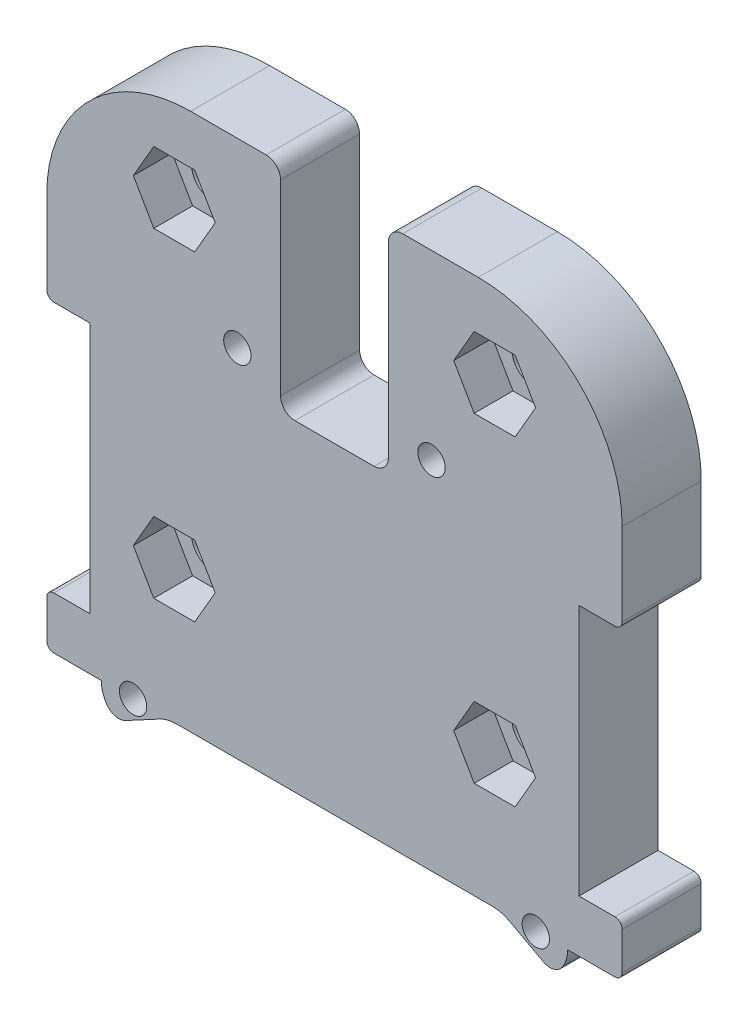
SolidWorks part; units mm, degrees
ref_plane "前视基准面" through (0, 0, 0) normal (0, 0, 1) x (1, 0, 0)
ref_plane "上视基准面" through (0, 0, 0) normal (0, 1, 0) x (1, 0, 0)
ref_plane "右视基准面" through (0, 0, 0) normal (1, 0, 0) x (0, 0, -1)
sketch "草图1" plane through (0, 0, 0) normal (0, 0, 1) x (1, 0, 0)
  line L0 (0, 0) -> (0, 36.8895) construction
  line L2 (-40, 50) -> (40, 50)
  line L3 (-40, 50) -> (-40, -50)
  line L4 (-40, -50) -> (40, -50)
  line L5 (40, 50) -> (40, -50)
  dimension "D1" = 80
  dimension "D2" = 100
  dimension "D3" = 40
  dimension "D4" = 50
extrude "凸台-拉伸1" add sketch "草图1" along normal blind 11 contours L2 L5 L4 L3
sketch "草图7" plane through (0, 0, 11) normal (0, 0, 1) x (1, 0, 0)
  line L0 (0, 0) -> (0, 50) construction
  line L1 (-40, 50) -> (40, 50) construction
  line L3 (-7.5, 50) -> (7.5, 50)
  line L4 (-7.5, 50) -> (-7.5, 20)
  line L5 (-7.5, 20) -> (7.5, 20)
  line L6 (7.5, 50) -> (7.5, 20)
  dimension "D1" = 30
  dimension "D2" = 15
  dimension "D3" = 7.5
extrude "切除-拉伸1" cut sketch "草图7" against normal blind 16
sketch "草图2" plane through (0, 0, 11) normal (0, 0, 1) x (1, 0, 0)
  line L0 (0, 0) -> (0, -50) construction
  line L1 (-40, -50) -> (40, -50) construction
  line L2 (-23.6474, -14.5) -> (32.5152, -14.5) construction
  line L3 (-25.0117, -34.5) -> (44.0357, -34.5) construction
  line L4 (-19.0329, -14.5) -> (-17.8955, -14.5)
  line L5 (17.8955, -14.5) -> (19.0329, -14.5)
  line L6 (17.8955, -34.5) -> (19.0329, -34.5)
  line L7 (-19.0329, -34.5) -> (-17.8955, -34.5)
  arc A0 (-17.8955, -14.5) -> (-17.8955, -34.5) centre (0, -24.5) ccw
  arc A1 (-19.0329, -14.5) -> (-19.0329, -34.5) centre (0, -24.5) ccw
  arc A2 (17.8955, -34.5) -> (17.8955, -14.5) centre (0, -24.5) ccw
  arc A3 (19.0329, -34.5) -> (19.0329, -14.5) centre (0, -24.5) ccw
  dimension "D1" = 25.5
  dimension "D2" = 10
  dimension "D4" = 21.5
  dimension "D5" = 20.5
  dimension "D3" = 20
sketch "草图5" plane through (0, 0, 0) normal (0, 0, -1) x (-1, 0, 0)
  line L0 (0, 30) -> (0, -50) construction
  line L2 (40, -50) -> (-40, -50) construction
  point P6 (-13.5, 24.75)
  point P7 (-28, -24.75)
  point P8 (28, -24.75)
  point P9 (13.5, 24.75)
  dimension "D1" = 13.5
  dimension "D2" = 28
  dimension "D3" = 49.5
  dimension "D4" = 24.75
hole_wizard "M4 螺纹孔1" positions "3D草图2" profile "草图6" tap size "M4" standard "GB" end condition up to next
sketch3d "3D草图2"
  point P0 (13.5, 24.75, 0)
  point P3 (-13.5, 24.75, 0)
  point P6 (-28, -24.75, 0)
  point P9 (28, -24.75, 0)
sketch "草图6" plane through (13.5, 24.75, 0) normal (1, 0, 0) x (0, 1, 0)
  line L0 (0, 0) -> (0, 11)
  line L1 (0, 11) -> (1.65, 11)
  line L2 (1.65, 11) -> (1.65, 0.375)
  line L3 (1.65, 0.375) -> (2.025, 0)
  line L5 (2.025, 0) -> (0, 0)
  line L6 (-1.65, 0.375) -> (-2.025, 0) construction
  line L11 (0, -6.35) -> (0, 107.95) construction
  dimension "通孔螺纹孔钻头直径" = 3.3
  dimension "通孔螺纹孔钻头深度" = 11
  dimension "近端锥形沉头孔直径" = 4.05
  dimension "近端锥形沉头孔角度" = 90
cosmetic thread "孔螺蚊线1" parameters "D2"=4
cosmetic thread "孔螺蚊线2" parameters "D2"=4
cosmetic thread "孔螺蚊线3" parameters "D2"=4
cosmetic thread "孔螺蚊线4" parameters "D2"=4
fillet "圆角1" radius 20 2 edges at (40, 50, 5.5) (-40, 50, 5.5)
fillet "圆角2" radius 2 6 edges at (40, -50, 5.5) (-40, -50, 5.5) (-7.5, 50, 5.5) (-7.5, 20, 5.5) (7.5, 20, 5.5) (7.5, 50, 5.5)
sketch "草图9" plane through (0, 0, 0) normal (0, 0, 1) x (1, 0, 0)
  line L0 (40, 17.5) -> (34, 17.5)
  line L1 (40, 30) -> (40, -48) construction
  line L2 (34, 17.5) -> (34, -17.5)
  line L3 (40, 17.5) -> (40, -17.5)
  line L4 (0, 0) -> (46.0009, 0) construction
  line L5 (40, -17.5) -> (34, -17.5)
  line L6 (0, 0) -> (0, 43.2165) construction
  line L7 (-40, -17.5) -> (-34, -17.5)
  line L8 (-34, 17.5) -> (-34, -17.5)
  line L9 (-40, 17.5) -> (-34, 17.5)
  line L10 (-40, 17.5) -> (-40, -17.5)
  point P12 (34, 0)
  dimension "D1" = 35
  dimension "D2" = 6
extrude "切除-拉伸2" cut sketch "草图9" along normal blind 11
sketch "草图11" plane through (0, 0, 0) normal (0, 0, 1) x (1, 0, 0)
  line L0 (0, 36.6897) -> (0, -57.9108) construction
  line L1 (0, 30) -> (0, -50) construction
  line L2 (0, 16) -> (-52.3712, 16) construction
  line L3 (0, 16) -> (-36.4685, 52.4685) construction
  circle A0 centre (0, 16) radius 31.5 construction
  circle A1 centre (-22.2739, 38.2739) radius 3
  circle A2 centre (22.2739, 38.2739) radius 3
  circle A3 centre (22.2739, -6.2739) radius 3
  circle A4 centre (-22.2739, -6.2739) radius 3
  point P20 (0, 16)
  dimension "D1" = 63
  dimension "D4" = 6
  dimension "D2" = 16
  dimension "D3" = 45
  dimension "D5" = 4
extrude "切除-拉伸4" cut sketch "草图11" along normal blind 15
sketch "草图12" plane through (0, 0, 0) normal (0, 0, 1) x (1, 0, 0)
  line L0 (0, 41.1031) -> (0, -79.5039) construction
  circle A4 centre (13.5, 24.75) radius 3.43
  circle A5 centre (28, -24.75) radius 3.43
  circle A6 centre (-28, -24.75) radius 3.43
  circle A7 centre (-13.5, 24.75) radius 3.43
  dimension "D1" = 6.86
  dimension "D2" = 6.86
extrude "切除-拉伸5" cut sketch "草图12" along normal blind 3.9
sketch "草图13" plane through (0, 0, 11) normal (0, 0, 1) x (1, 0, 0)
  line L0 (0, 30) -> (0, -54.2815) construction
  line L1 (-19.4275, 33.3439) -> (-16.5812, 38.2739)
  line L2 (-16.5812, 38.2739) -> (-19.4275, 43.2039)
  line L3 (-19.4275, 43.2039) -> (-25.1202, 43.2039)
  line L4 (-25.1202, 43.2039) -> (-27.9665, 38.2739)
  line L5 (-27.9665, 38.2739) -> (-25.1202, 33.3439)
  line L6 (-25.1202, 33.3439) -> (-19.4275, 33.3439)
  line L7 (-19.4275, -11.2039) -> (-16.5812, -6.2739)
  line L8 (-16.5812, -6.2739) -> (-19.4275, -1.3439)
  line L9 (-19.4275, -1.3439) -> (-25.1202, -1.3439)
  line L10 (-25.1202, -1.3439) -> (-27.9665, -6.2739)
  line L11 (-27.9665, -6.2739) -> (-25.1202, -11.2039)
  line L12 (-25.1202, -11.2039) -> (-19.4275, -11.2039)
  line L13 (25.1202, -11.2039) -> (19.4275, -11.2039)
  line L14 (27.9665, -6.2739) -> (25.1202, -11.2039)
  line L15 (25.1202, -1.3439) -> (27.9665, -6.2739)
  line L16 (19.4275, -1.3439) -> (25.1202, -1.3439)
  line L17 (16.5812, -6.2739) -> (19.4275, -1.3439)
  line L18 (19.4275, -11.2039) -> (16.5812, -6.2739)
  line L19 (25.1202, 33.3439) -> (19.4275, 33.3439)
  line L20 (27.9665, 38.2739) -> (25.1202, 33.3439)
  line L21 (25.1202, 43.2039) -> (27.9665, 38.2739)
  line L22 (19.4275, 43.2039) -> (25.1202, 43.2039)
  line L23 (16.5812, 38.2739) -> (19.4275, 43.2039)
  line L24 (19.4275, 33.3439) -> (16.5812, 38.2739)
  circle A0 centre (-22.2739, 38.2739) radius 4.93 construction
  circle A1 centre (-22.2739, -6.2739) radius 4.93 construction
  circle A2 centre (22.2739, -6.2739) radius 4.93 construction
  circle A3 centre (22.2739, 38.2739) radius 4.93 construction
  dimension "D1" = 9.86
  dimension "D2" = 9.86
extrude "切除-拉伸6" cut sketch "草图13" against normal blind 5.4
sketch "草图14" plane through (0, 0, 0) normal (0, 0, -1) x (-1, 0, 0)
  line L0 (-28, -24.75) -> (52.474, -24.75) construction
  line L1 (0, 0) -> (0, -65.5575) construction
  line L2 (-42.2815, -24.75) -> (-32.43, -24.75)
  line L3 (-42.2815, -24.75) -> (-42.2815, -58.5485)
  line L4 (-42.2815, -58.5485) -> (45.7714, -58.5485)
  line L5 (45.7714, -24.75) -> (45.7714, -58.5485)
  line L6 (-21.948, -24.75) -> (21.948, -24.75)
  line L7 (32.43, -24.75) -> (45.7714, -24.75)
  line L8 (-24.315, -25.3458) -> (-29.053, -27.8922)
  line L9 (24.315, -25.3458) -> (29.053, -27.8922)
  arc A0 (-32.43, -24.75) -> (-31.6457, -27.2666) centre (-28, -24.75) ccw
  circle A1 centre (-28, -24.75) radius 3.43 construction
  arc A2 (32.43, -24.75) -> (31.6457, -27.2666) centre (28, -24.75) cw
  arc A3 (-31.6457, -27.2666) -> (-29.053, -27.8922) centre (-29.9998, -26.1305) ccw
  arc A4 (-21.948, -24.75) -> (-24.315, -25.3458) centre (-21.948, -29.75) ccw
  arc A5 (21.948, -24.75) -> (24.315, -25.3458) centre (21.948, -29.75) cw
  arc A6 (31.6457, -27.2666) -> (29.053, -27.8922) centre (29.9998, -26.1305) cw
  point P9 (-30.2831, -28.4996)
  point P19 (-30.1499, -28.5775)
  point P22 (-30.277, -28.55)
  point P25 (-23.2065, -24.75)
  dimension "D1" = 1
  dimension "D3" = 2
  dimension "D4" = 5
  dimension "D2" = 3.8
extrude "切除-拉伸7" cut sketch "草图14" against normal blind 14
sketch "草图15" plane through (0, 0, 11) normal (0, 0, 1) x (1, 0, 0)
  line L0 (0, 0) -> (0, 55.0159) construction
  circle A0 centre (-13.5, 24.75) radius 1.9
  circle A1 centre (-28, -24.75) radius 1.9
  circle A2 centre (13.5, 24.75) radius 1.9
  circle A3 centre (28, -24.75) radius 1.9
  dimension "D1" = 3.8
  dimension "D2" = 3.8
extrude "切除-拉伸8" cut sketch "草图15" against normal blind 14
fillet "圆角4" radius 0.12 4 edges at (-29.1996, -27.9634, 1.95) (-24.6602, -25.5313, 1.95) (24.6602, -25.5313, 1.95) (29.1996, -27.9634, 1.95)
fillet "圆角5" radius 1 6 edges at (-40, 17.5, 5.5) (-40, -17.5, 5.5) (-40, -24.75, 5.5) (40, -24.75, 5.5) (40, -17.5, 5.5) (40, 17.5, 5.5)
